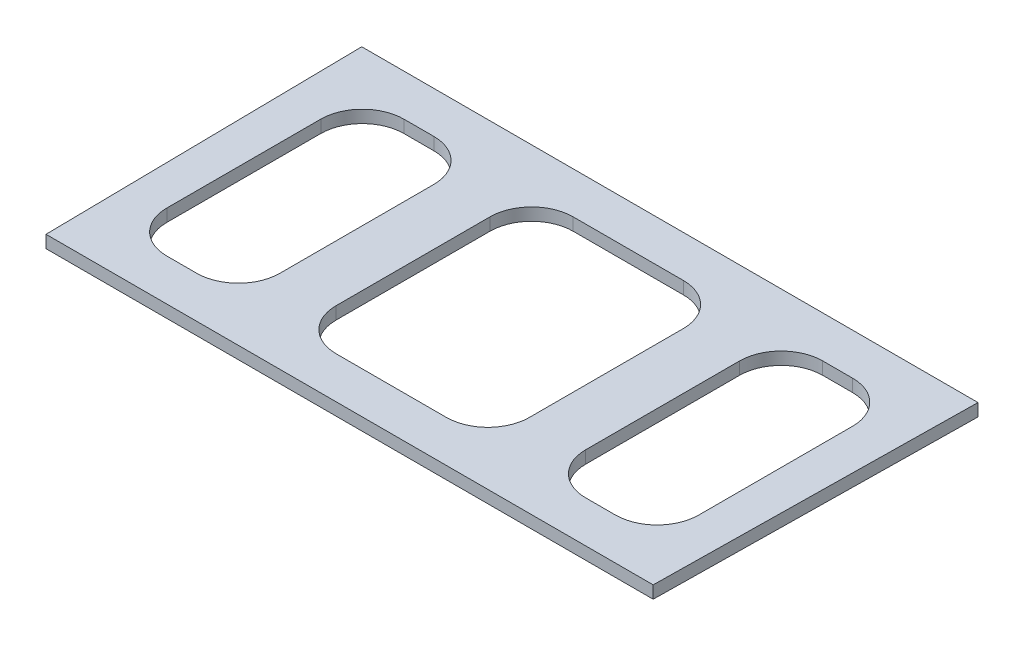
SolidWorks part; units mm, degrees
ref_plane "Front Plane" through (0, 0, 0) normal (0, 0, 1) x (1, 0, 0)
ref_plane "Top Plane" through (0, 0, 0) normal (0, 1, 0) x (1, 0, 0)
ref_plane "Right Plane" through (0, 0, 0) normal (1, 0, 0) x (0, 0, -1)
sketch "Sketch1" plane through (0, 0, 0) normal (0, 1, 0) x (1, 0, 0)
  line L0 (-72.9864, 0) -> (72.9864, 0)
  line L1 (-72.9864, 0) -> (-74.075, 77)
  line L2 (-74.075, 77) -> (74.075, 77)
  line L3 (74.075, 77) -> (72.9864, 0)
  point P4 (0, 0)
  dimension "D1" = 89.19
  dimension "D2" = 89.19
  dimension "D3" = 148.15
  dimension "D4" = 77
extrude "Boss-Extrude1" add sketch "Sketch1" along normal blind 3
sketch "Sketch2" plane through (0, 3, 0) normal (0, 1, 0) x (1, 0, 0)
  line L0 (-74.075, 77) -> (-72.9864, 0) construction
  line L1 (-30, -70.8527) -> (30, -70.8527) construction
  line L2 (-30, -70.8527) -> (-30, 70.8527) construction
  line L3 (-30, 70.8527) -> (30, 70.8527) construction
  line L4 (30, -70.8527) -> (30, 70.8527) construction
  line L5 (-30, -70.8527) -> (30, 70.8527) construction
  line L6 (-30, 70.8527) -> (30, -70.8527) construction
  line L7 (-36.75, -82.8936) -> (36.75, -82.8936) construction
  line L8 (-36.75, -82.8936) -> (-36.75, 82.8936) construction
  line L9 (-36.75, 82.8936) -> (36.75, 82.8936) construction
  line L10 (36.75, -82.8936) -> (36.75, 82.8936) construction
  line L11 (-36.75, -82.8936) -> (36.75, 82.8936) construction
  line L12 (-36.75, 82.8936) -> (36.75, -82.8936) construction
  line L13 (-46.75, 67) -> (-53.9326, 67)
  line L14 (-36.75, 57) -> (-36.75, 20)
  line L15 (-46.75, 10) -> (-53.9326, 10)
  line L16 (-63.9326, 57) -> (-63.9326, 20)
  line L21 (-23.25, -65.2871) -> (23.25, -65.2871) construction
  line L22 (-23.25, -65.2871) -> (-23.25, 65.2871) construction
  line L23 (-23.25, 65.2871) -> (23.25, 65.2871) construction
  line L24 (23.25, -65.2871) -> (23.25, 65.2871) construction
  line L25 (-23.25, -65.2871) -> (23.25, 65.2871) construction
  line L26 (-23.25, 65.2871) -> (23.25, -65.2871) construction
  line L31 (30.7785, -8.8097) -> (-23.25, 64.0404) construction
  line L32 (30.7785, 53.8892) -> (-15.7215, -8.8097) construction
  line L33 (-13.25, 67) -> (0, 67)
  line L34 (-23.25, 57) -> (-23.25, 20)
  line L35 (-13.25, 10) -> (0, 10)
  line L36 (0, 67) -> (0, 10)
  line L37 (74.075, 77) -> (-74.075, 77) construction
  line L38 (-72.9864, 0) -> (72.9864, 0) construction
  arc A0 (-23.25, 20) -> (-13.25, 10) centre (-13.25, 20) ccw
  arc A1 (-13.25, 67) -> (-23.25, 57) centre (-13.25, 57) ccw
  arc A2 (-46.75, 67) -> (-36.75, 57) centre (-46.75, 57) cw
  arc A3 (-36.75, 20) -> (-46.75, 10) centre (-46.75, 20) cw
  arc A4 (-53.9326, 10) -> (-63.9326, 20) centre (-53.9326, 20) cw
  arc A5 (-53.9326, 67) -> (-63.9326, 57) centre (-53.9326, 57) ccw
  point P0 (0, 0)
  point P5 (0, 0)
  point P14 (0, 0)
  point P19 (7.5285, 22.5398)
  point P28 (-0.5568, 68.5377)
  point P36 (0, 0)
  point P41 (-23.25, 67)
  point P44 (-36.75, 67)
  point P51 (-63.9326, 67)
  dimension "D7" = 10
  dimension "D1" = 60
  dimension "D2" = 6.75
  dimension "D3" = 6.75
  dimension "D4" = 10
  dimension "D5" = 10
  dimension "D6" = 10
extrude "Cut-Extrude1" cut sketch "Sketch2" against normal blind 10
mirror "Mirror1" about plane through (0, 0, 0) normal (1, 0, 0) of "Cut-Extrude1"
equation "\"D3@Sketch2\"=\"D2@Sketch2\""
